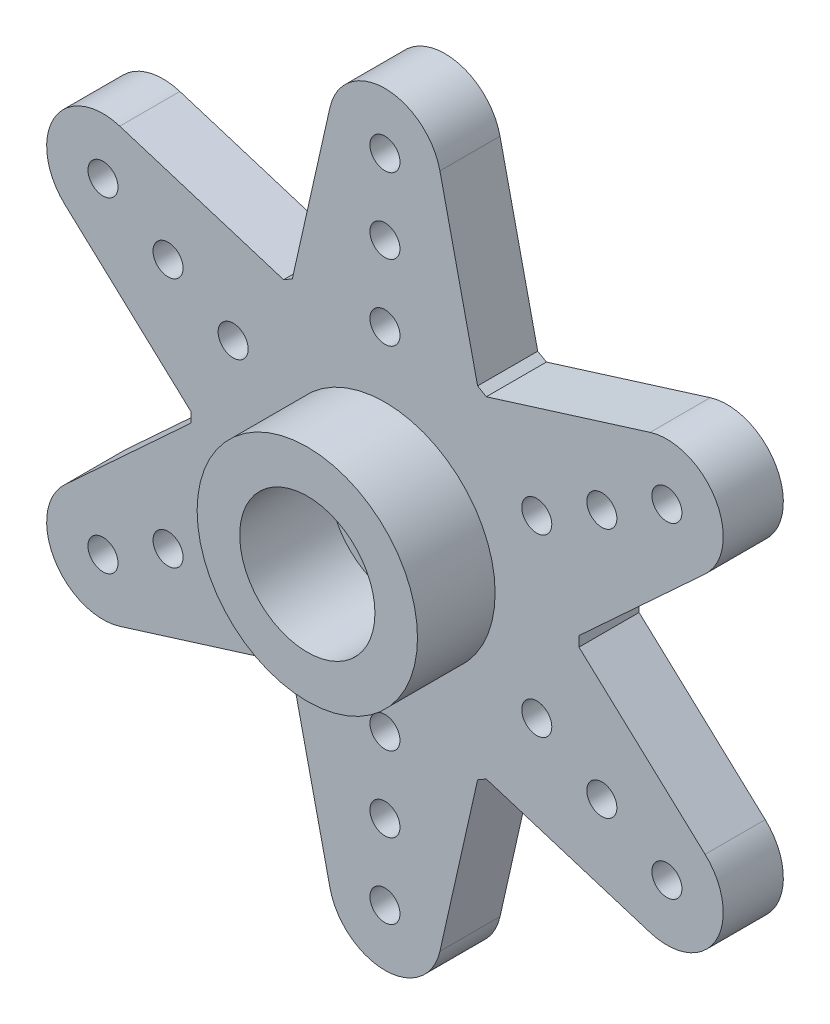
SolidWorks part; units mm, degrees
ref_plane "Ebene vorne" through (0, 0, 0) normal (0, 0, 1) x (1, 0, 0)
ref_plane "Ebene oben" through (0, 0, 0) normal (0, 1, 0) x (1, 0, 0)
ref_plane "Ebene rechts" through (0, 0, 0) normal (1, 0, 0) x (0, 0, -1)
sketch "Skizze1" plane through (0, 0, 0) normal (0, 0, 1) x (1, 0, 0)
  line L0 (0, 0) -> (0, 13) construction
  line L1 (-3.7, 6.8097) -> (-2.1951, 13.4942)
  line L2 (3.7, 6.8097) -> (2.1951, 13.4942)
  line L3 (4.0474, 6.6092) -> (10.5888, 8.6481)
  line L4 (7.7474, 0.2006) -> (12.7838, 4.8461)
  line L5 (7.7474, -0.2006) -> (12.7838, -4.8461)
  line L6 (4.0474, -6.6092) -> (10.5888, -8.6481)
  line L7 (3.7, -6.8097) -> (2.1951, -13.4942)
  line L8 (-3.7, -6.8097) -> (-2.1951, -13.4942)
  line L9 (-4.0474, -6.6092) -> (-10.5888, -8.6481)
  line L10 (-7.7474, -0.2006) -> (-12.7838, -4.8461)
  line L11 (-7.7474, 0.2006) -> (-12.7838, 4.8461)
  line L12 (-4.0474, 6.6092) -> (-10.5888, 8.6481)
  line L13 (3.7, 6.8097) -> (4.0474, 6.6092)
  line L14 (7.7474, 0.2006) -> (7.7474, -0.2006)
  line L15 (4.0474, -6.6092) -> (3.7, -6.8097)
  line L16 (-3.7, -6.8097) -> (-4.0474, -6.6092)
  line L17 (-7.7474, -0.2006) -> (-7.7474, 0.2006)
  line L18 (-4.0474, 6.6092) -> (-3.7, 6.8097)
  circle A0 centre (0, 0) radius 1.5
  circle A1 centre (0, 13) radius 0.6
  circle A2 centre (0, 10) radius 0.6
  circle A3 centre (0, 7) radius 0.6
  circle A4 centre (0, 0) radius 7.75 construction
  arc A5 (2.1951, 13.4942) -> (-2.1951, 13.4942) centre (0, 13) ccw
  arc A6 (12.7838, 4.8461) -> (10.5888, 8.6481) centre (11.2583, 6.5) ccw
  circle A7 centre (6.0622, 3.5) radius 0.6
  circle A8 centre (8.6603, 5) radius 0.6
  circle A9 centre (11.2583, 6.5) radius 0.6
  arc A10 (10.5888, -8.6481) -> (12.7838, -4.8461) centre (11.2583, -6.5) ccw
  circle A11 centre (6.0622, -3.5) radius 0.6
  circle A12 centre (8.6603, -5) radius 0.6
  circle A13 centre (11.2583, -6.5) radius 0.6
  arc A14 (-2.1951, -13.4942) -> (2.1951, -13.4942) centre (0, -13) ccw
  circle A15 centre (0, -7) radius 0.6
  circle A16 centre (0, -10) radius 0.6
  circle A17 centre (0, -13) radius 0.6
  arc A18 (-12.7838, -4.8461) -> (-10.5888, -8.6481) centre (-11.2583, -6.5) ccw
  circle A19 centre (-6.0622, -3.5) radius 0.6
  circle A20 centre (-8.6603, -5) radius 0.6
  circle A21 centre (-11.2583, -6.5) radius 0.6
  arc A22 (-10.5888, 8.6481) -> (-12.7838, 4.8461) centre (-11.2583, 6.5) ccw
  circle A23 centre (-6.0622, 3.5) radius 0.6
  circle A24 centre (-8.6603, 5) radius 0.6
  circle A25 centre (-11.2583, 6.5) radius 0.6
  point P67 (0, 0)
  dimension "D1" = 3
  dimension "D2" = 1.2
  dimension "D6" = 15.5
  dimension "D7" = 4.5
  dimension "D9" = 6
  dimension "D3" = 13
  dimension "D4" = 3
  dimension "D5" = 3
  dimension "D8" = 7.4
extrude "Aufsatz-Linear austragen1" add sketch "Skizze1" along normal blind 2.4
sketch "Skizze2" plane through (0, 0, 2.4) normal (0, 0, 1) x (1, 0, 0)
  circle A0 centre (0, 0) radius 1.5
  circle A1 centre (0, 0) radius 4.4
  circle A2 centre (0, 0) radius 1.5 construction
  dimension "D1" = 8.8
extrude "Aufsatz-Linear austragen2" add sketch "Skizze2" along normal blind 3.1
sketch "Skizze4" plane through (0, 0, 5.5) normal (0, 0, 1) x (1, 0, 0)
  circle A0 centre (0, 0) radius 2.7
  dimension "D1" = 5.4
extrude "Schnitt-Linear austragen1" cut sketch "Skizze4" against normal blind 3.6
